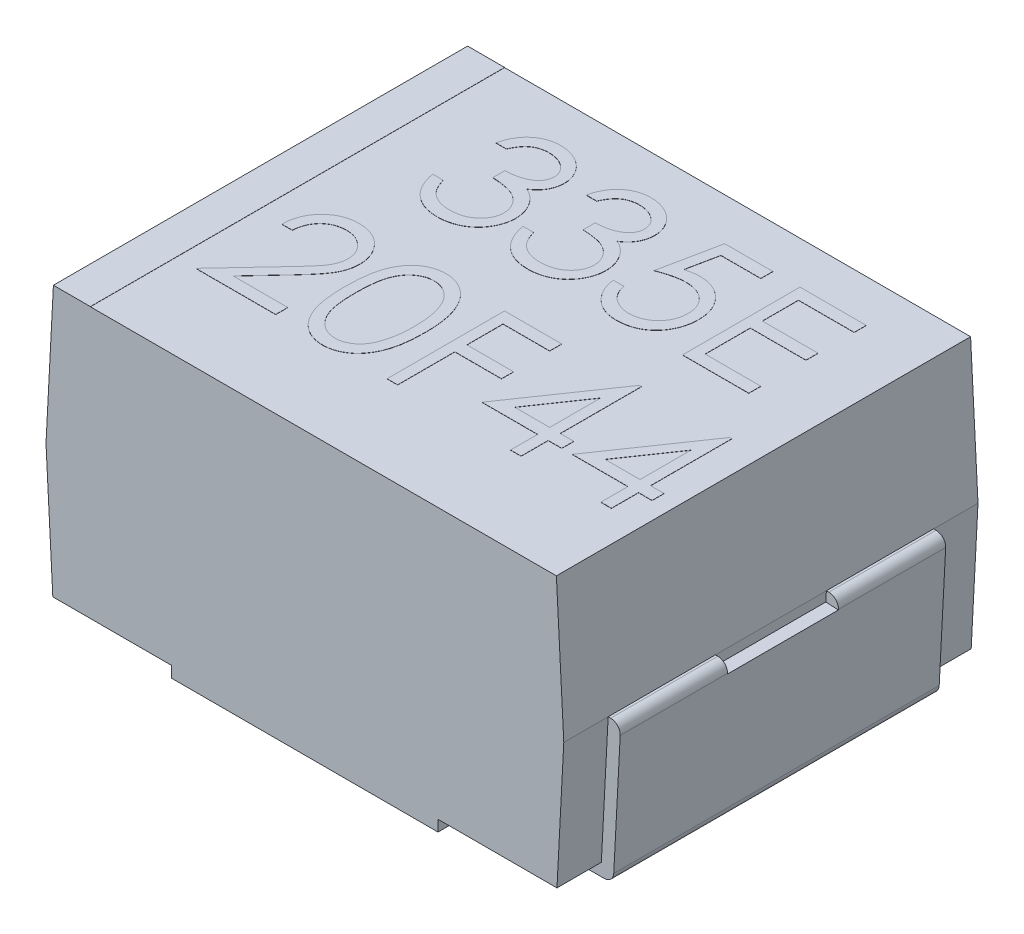
SolidWorks part; units mm, degrees
ref_plane "Front Plane" through (0, 0, 0) normal (0, 0, 1) x (1, 0, 0)
ref_plane "Top Plane" through (0, 0, 0) normal (0, 1, 0) x (1, 0, 0)
ref_plane "Right Plane" through (0, 0, 0) normal (1, 0, 0) x (0, 0, -1)
sketch "Sketch1" plane through (0, 0, 0) normal (0, 0, 1) x (1, 0, 0)
  line L0 (-1.75, 0) -> (1.75, 0) construction
  line L1 (-1.7, 0.95) -> (1.7, 0.95)
  line L3 (-1.7, -0.95) -> (1.7, -0.95)
  line L5 (-1.75, 0.95) -> (1.75, -0.95) construction
  line L6 (-1.75, -0.95) -> (1.75, 0.95) construction
  line L7 (-1.75, 0) -> (-1.7, 0.95)
  line L9 (-1.7, -0.95) -> (-1.75, 0)
  line L10 (1.7, 0.95) -> (1.75, 0)
  line L11 (1.75, 0) -> (1.7, -0.95)
  point P0 (0, 0)
  dimension "D1" = 1.9
  dimension "D2" = 3.5
  dimension "D3" = 0.05
  dimension "D4" = 0.05
  dimension "D5" = 3.4
  dimension "D6" = 3.4
  dimension "D7" = 1.9
  dimension "D8" = 93.013
  dimension "D9" = 1.75
  dimension "D10" = 1.75
  dimension "D11" = 93.013
extrude "Boss-Extrude1" add sketch "Sketch1" along normal mid plane 2.8
sketch "Sketch2" plane through (0, 0, 1.4) normal (0, 0, 1) x (1, 0, 0)
  line L0 (-1.7, -0.95) -> (-0.9, -0.95)
  line L1 (-1.7, -0.95) -> (1.7, -0.95) construction
  line L2 (-0.9, -0.95) -> (-0.9, -0.875)
  line L3 (-0.9, -0.875) -> (-1.7039, -0.875)
  line L4 (-1.75, 0) -> (-1.7, -0.95) construction
  line L5 (-1.7039, -0.875) -> (-1.7, -0.95)
  line L6 (1.7, -0.95) -> (0.9, -0.95)
  line L7 (0.9, -0.95) -> (0.9, -0.875)
  line L8 (0.9, -0.875) -> (1.7039, -0.875)
  line L9 (1.7, -0.95) -> (1.75, 0) construction
  line L10 (1.7039, -0.875) -> (1.7, -0.95)
  dimension "D1" = 0.8
  dimension "D2" = 0.8
  dimension "D3" = 0.075
  dimension "D4" = 0.075
extrude "Cut-Extrude1" cut sketch "Sketch2" against normal up to next
sketch "Sketch3" plane through (0, 0, 0) normal (0, 0, 1) x (1, 0, 0)
  line L0 (-1.75, 0) -> (-1.7039, -0.875)
  line L1 (-1.7039, -0.875) -> (-0.94, -0.875)
  line L2 (-0.9, -0.875) -> (-1.7039, -0.875) construction
  line L3 (-0.94, -0.875) -> (-0.94, -0.895)
  line L4 (-1.005, -0.96) -> (-1.7228, -0.96)
  line L5 (-1.7877, -0.8984) -> (-1.8314, -0.0684)
  line L6 (-1.7665, 0) -> (-1.75, 0)
  line L7 (-0.9, -0.95) -> (-0.9, -0.875) construction
  arc A0 (-1.8314, -0.0684) -> (-1.7665, 0) centre (-1.7665, -0.065) cw
  arc A1 (-0.94, -0.895) -> (-1.005, -0.96) centre (-1.005, -0.895) cw
  arc A2 (-1.7228, -0.96) -> (-1.7877, -0.8984) centre (-1.7228, -0.895) cw
  point P14 (-1.835, 0)
  point P17 (-0.94, -0.96)
  dimension "D4" = 0.065
  dimension "D1" = 0.085
  dimension "D2" = 0.085
  dimension "D3" = 0.04
extrude "Boss-Extrude2" add sketch "Sketch3" along normal mid plane 2.2 separate body
mirror "Mirror1" about plane through (0, 0, 0) normal (1, 0, 0) of bodies 103
sketch "Sketch4" plane through (-1.7452, -0.0919, 0) normal (-0.9986, -0.0526, 0) x (0, 0, 1)
  line L0 (1.4, 0.092) -> (-1.4, 0.092) construction
  line L1 (-0.65, 0.692) -> (0.65, 0.692)
  line L2 (-0.65, 0.692) -> (-0.65, -0.508)
  line L3 (-0.65, -0.508) -> (0.65, -0.508)
  line L4 (0.65, 0.692) -> (0.65, -0.508)
  line L5 (-0.65, 0.692) -> (0.65, -0.508) construction
  line L6 (-0.65, -0.508) -> (0.65, 0.692) construction
  point P0 (0, 0.092)
  dimension "D1" = 1.2
  dimension "D2" = 1.3
extrude "Cut-Extrude2" cut sketch "Sketch4" along normal up to surface (0.0849 mm away) up to face at (-1.8096, -0.4834, 0)
sketch "Sketch5" plane through (0, 0.95, 0) normal (0, 1, 0) x (1, 0, 0)
  line L0 (1.7, -1.4) -> (-1.7, -1.4) construction
  line L1 (-1.7, 1.4) -> (-1.45, 1.4)
  line L2 (-1.7, 1.4) -> (-1.7, -1.4)
  line L3 (-1.7, -1.4) -> (-1.45, -1.4)
  line L4 (-1.45, 1.4) -> (-1.45, -1.4)
  dimension "D1" = 0.25
extrude "Boss-Extrude3" add sketch "Sketch5" along normal blind 0.0013
sketch "Sketch6" plane through (0, 0.95, 0) normal (0, 1, 0) x (1, 0, 0)
  line L0 (-1.0991, 0.3185) -> (1.4991, 0.3185) construction
  text T0 "335E" font "Century Gothic" height in points 3
extrude "Boss-Extrude4" add sketch "Sketch6" along normal blind 0.0013 separate body
sketch "Sketch7" plane through (0, 0.95, 0) normal (0, 1, 0) x (1, 0, 0)
  line L0 (-1.3477, -0.8195) -> (1.371, -0.8195) construction
  text T0 "20F44" font "Century Gothic" height in points 3
extrude "Boss-Extrude5" add sketch "Sketch7" along normal blind 0.0013 separate body
sketch "Sketch8" plane through (1.7452, -0.0919, 0) normal (0.9986, -0.0526, 0) x (0, 0, -1)
  line L0 (-1.4, 0.092) -> (1.4, 0.092) construction
  line L1 (-0.375, 0.1595) -> (0.375, 0.1595)
  line L2 (-0.375, 0.1595) -> (-0.375, 0.0245)
  line L3 (-0.375, 0.0245) -> (0.375, 0.0245)
  line L4 (0.375, 0.1595) -> (0.375, 0.0245)
  line L5 (-0.375, 0.1595) -> (0.375, 0.0245) construction
  line L6 (-0.375, 0.0245) -> (0.375, 0.1595) construction
  point P0 (0, 0.092)
  dimension "D1" = 0.135
  dimension "D2" = 0.75
extrude "Cut-Extrude3" cut sketch "Sketch8" along normal up to surface (0.0849 mm away) up to face at (1.8096, -0.4834, 0)
